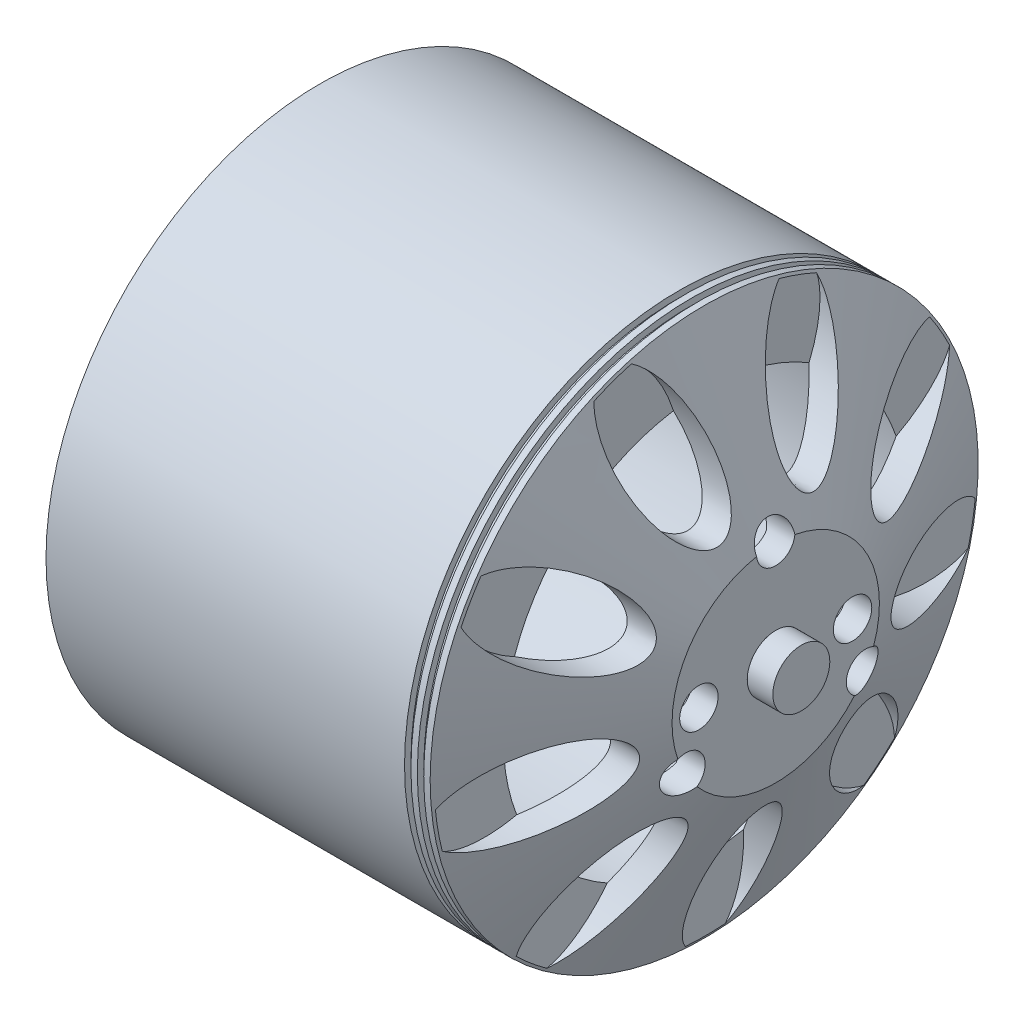
SolidWorks part; units mm, degrees
ref_plane "Front Plane" through (0, 0, 0) normal (0, 0, 1) x (1, 0, 0)
ref_plane "Top Plane" through (0, 0, 0) normal (0, 1, 0) x (1, 0, 0)
ref_plane "Right Plane" through (0, 0, 0) normal (1, 0, 0) x (0, 0, -1)
sketch "Sketch1" plane through (0, 0, 0) normal (0, 1, 0) x (1, 0, 0)
  line L0 (0, 0) -> (41.7529, 0)
  line L1 (36.7748, 2) -> (41.7529, 2)
  line L2 (41.7529, 8.0974) -> (36.1637, 21.4)
  line L3 (36.1637, 21.4) -> (35.6637, 21.4)
  line L4 (35.6637, 21.4) -> (35.6637, 20.9)
  line L5 (35.6637, 20.9) -> (35.1637, 20.9)
  line L6 (35.1637, 20.9) -> (35.1637, 21.4)
  line L7 (35.1637, 21.4) -> (34.6637, 21.4)
  line L8 (34.6637, 21.4) -> (34.6637, 20.9)
  line L9 (34.6637, 20.9) -> (34.1637, 20.9)
  line L10 (34.1637, 20.9) -> (34.1637, 21.4)
  line L11 (34.1637, 21.4) -> (6.1637, 21.4)
  line L13 (41.7529, 0) -> (43.7529, 0)
  line L17 (6.1637, 21.4) -> (6.1637, 19.4004)
  line L18 (6.1637, 19.4004) -> (33.7439, 19.4004)
  line L19 (43.7529, 0) -> (43.7529, 2)
  line L20 (43.7529, 2) -> (41.7529, 2)
  line L21 (39.728, 7.5) -> (34.728, 19.4004)
  line L22 (34.728, 19.4004) -> (33.7439, 19.4004)
  line L23 (39.728, 2.2247) -> (41.7529, 2.2247)
  line L24 (41.7529, 2.2247) -> (41.7529, 8.0974)
  line L25 (39.728, 7.5) -> (39.728, 3.4808)
  line L26 (41.7529, 2) -> (36.7748, 2)
  line L27 (36.7748, 2) -> (36.7748, 0)
  line L28 (36.7748, 0) -> (41.7529, 0)
  line L29 (39.728, 3.4808) -> (36.7748, 3.4808)
  line L30 (36.7748, 3.4808) -> (36.7748, 2.2247)
  line L31 (36.7748, 2.2247) -> (39.728, 2.2247)
revolve "Revolve2" add sketch "Sketch1" angle 360 about L0
sketch "Sketch2" plane through (41.7529, 0, 0) normal (1, 0, 0) x (0, 0, -1)
  circle A0 centre (0, 0) radius 8.0974 construction
  circle A1 centre (-7.0125, -4.0487) radius 1.5
  circle A2 centre (7.0125, -4.0487) radius 1.5
  circle A3 centre (0, 8.0974) radius 1.5
  circle A6 centre (6, 0) radius 1.5
  circle A7 centre (-6, 0) radius 1.5
extrude "Cut-Extrude2" cut sketch "Sketch2" against normal blind 10 contours A6 | A3 | A2 | A7 | A1
sketch "Sketch3" plane through (41.7529, 0, 0) normal (1, 0, 0) x (0, 0, -1)
  line L4 (0, 0) -> (0, -16)
  ellipse E2 centre (0, -16) end of major axis (0, -10) minor radius 3
extrude "Cut-Extrude6" cut sketch "Sketch3" against normal blind 5.5
pattern_circular "CirPattern1" count 9 every 40 about axis through (41.7529, 0, 0) along (-1, 0, 0) of "Cut-Extrude6"
sketch "Sketch4" plane through (41.7529, 0, 0) normal (1, 0, 0) x (0, 0, -1)
  circle A0 centre (0, 0) radius 2.2247
  circle A1 centre (0, 0) radius 2
extrude "Boss-Extrude1" add sketch "Sketch4" along normal blind 2 separate body
sketch "Sketch5" plane through (43.7529, 0, 0) normal (1, 0, 0) x (0, 0, -1)
  circle A0 centre (0, 0) radius 2
extrude "Boss-Extrude4" add sketch "Sketch5" against normal blind 7
